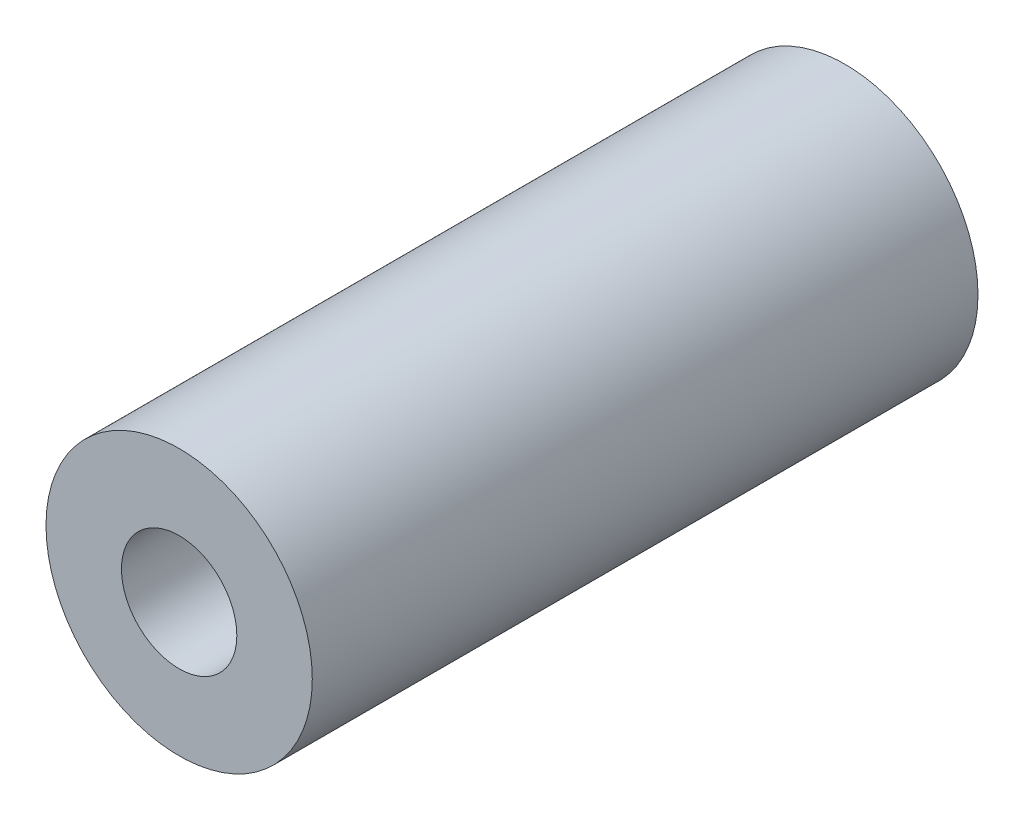
SolidWorks part; units mm, degrees
ref_plane "正面" through (0, 0, 0) normal (0, 0, 1) x (1, 0, 0)
ref_plane "平面" through (0, 0, 0) normal (0, 1, 0) x (1, 0, 0)
ref_plane "右側面" through (0, 0, 0) normal (1, 0, 0) x (0, 0, -1)
sketch "ｽｹｯﾁ1" plane through (0, 0, 0) normal (0, 0, 1) x (1, 0, 0)
  circle A0 centre (0, 0) radius 1.3
  circle A1 centre (0, 0) radius 3
  dimension "D1" = 6
  dimension "D2" = 2.6
extrude "ﾎﾞｽ - 押し出し1" add sketch "ｽｹｯﾁ1" along normal blind 15
